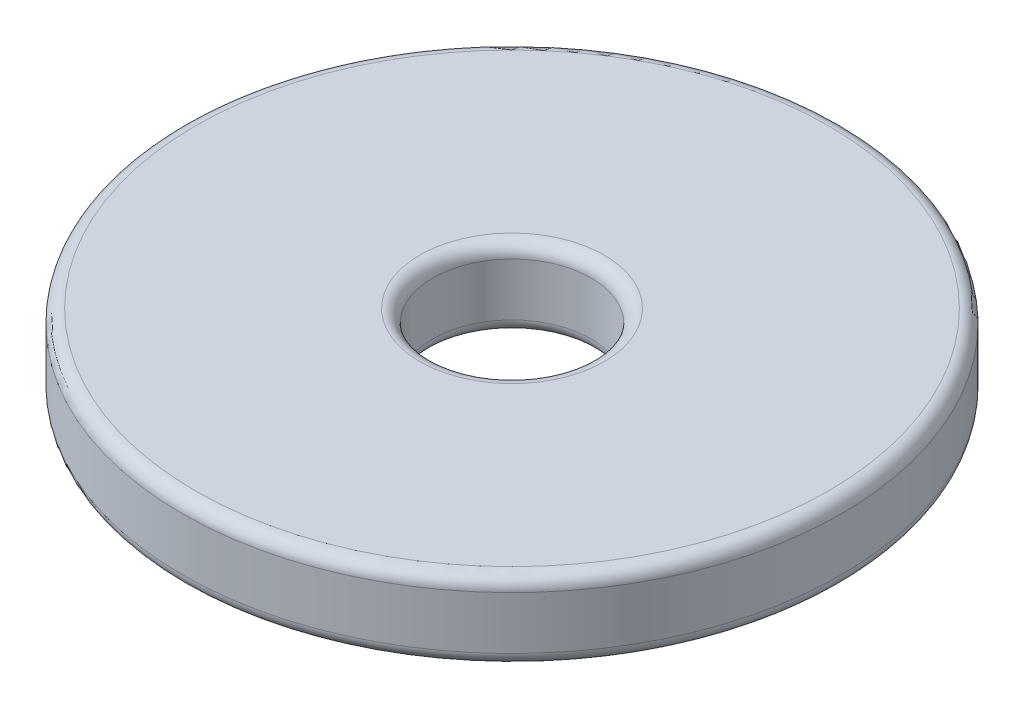
SolidWorks part; units mm, degrees
ref_plane "Alzado" through (0, 0, 0) normal (0, 0, 1) x (1, 0, 0)
ref_plane "Planta" through (0, 0, 0) normal (0, 1, 0) x (1, 0, 0)
ref_plane "Vista lateral" through (0, 0, 0) normal (1, 0, 0) x (0, 0, -1)
sketch "Croquis1" plane through (0, 0, 0) normal (0, 1, 0) x (1, 0, 0)
  circle A0 centre (0, 0) radius 12.5
  circle A1 centre (0, 0) radius 3
  dimension "D1" = 6
  dimension "D2" = 25
extrude "Saliente-Extruir1" add sketch "Croquis1" along normal blind 3
fillet "Redondeo1" radius 0.5 4 edges at (0, 0, 12.5) (0, 3, 12.5) (0, 0, 3) (0, 3, 3)
